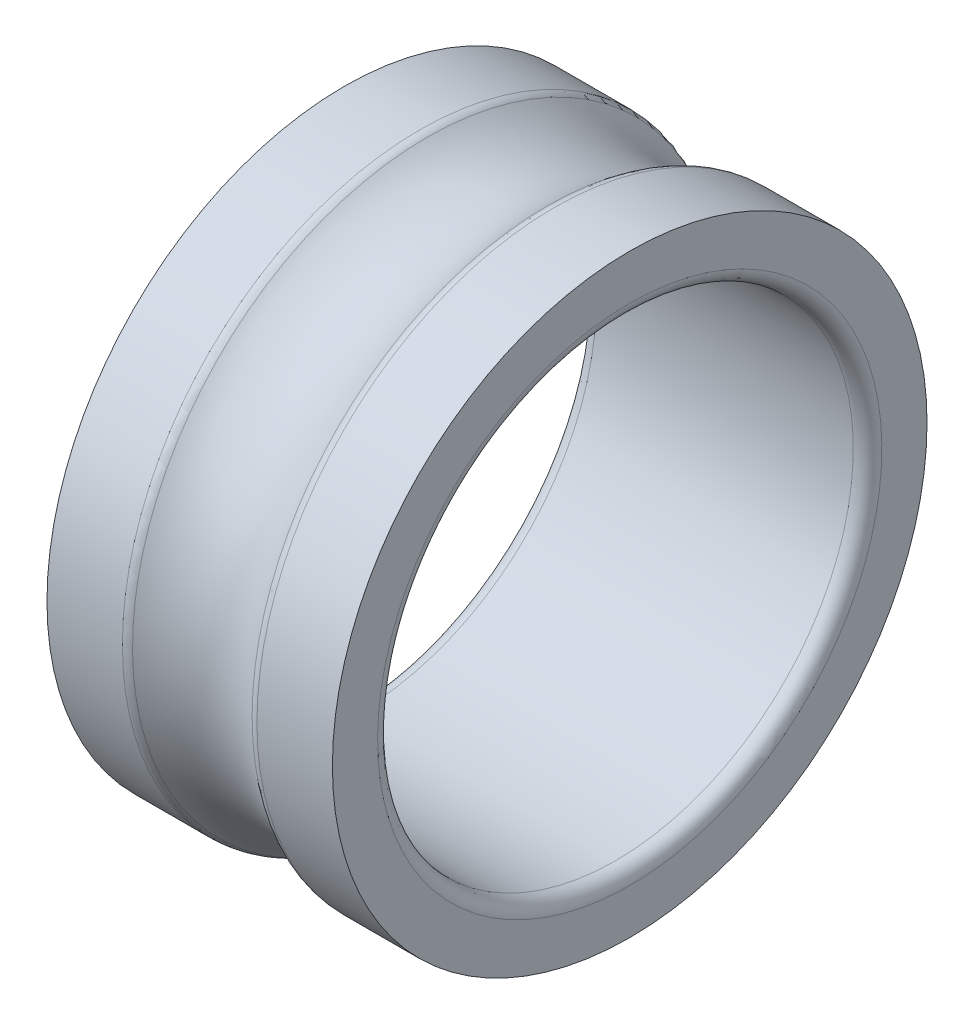
SolidWorks part; units mm, degrees
ref_plane "Front Plane" through (0, 0, 0) normal (0, 0, 1) x (1, 0, 0)
ref_plane "Top Plane" through (0, 0, 0) normal (0, 1, 0) x (1, 0, 0)
ref_plane "Right Plane" through (0, 0, 0) normal (1, 0, 0) x (0, 0, -1)
sketch "Sketch1" plane through (0, 0, 0) normal (0, 0, 1) x (1, 0, 0)
  line L0 (44.1264, 0) -> (-44.1264, 0) construction
  line L1 (-6, 10) -> (6, 10)
  line L2 (6, 10) -> (6, 12.5)
  line L3 (-6, 10) -> (-6, 12.5)
  line L4 (-6, 12.5) -> (6, 12.5)
  circle A0 centre (0, 15.5) radius 4
  point P2 (0, 0)
  point P9 (0, 10)
  dimension "D4" = 8
  dimension "D1" = 20
  dimension "D2" = 12
  dimension "D3" = 5.5
  dimension "D5" = 3
revolve "Revolve1" add sketch "Sketch1" angle 360 about L0
fillet "Fillet1" radius 0.6 2 edges at (6, 10, 0) (-6, 10, 0)
fillet "Fillet2" radius 0.5 2 edges at (2.6458, 12.5, 0) (-2.6458, 12.5, 0)
equation "\"d_ext_rouleau\"= 90"
equation "\"epaisseur_rouleau\"=80"
equation "\"alesage-rouleau\"= 52"
equation "\"jeu_dent_rouleau\"= 2"
equation "\"profondeur_dent_rouleau\"=4"
equation "\"n_dent_roueau\"= 15"
equation "\"d_ext_roulement_rouleau\"= 42"
equation "\"d_int_roulement_rouleau\"= 20"
equation "\"B_roulement_rouleau\"= 12"
equation "\"d_bille_roulement_rouleau\"= 8"
equation "\"F_anneau_alesage_rouleau\"=1.85"
equation "\"G_anneau_alesage_rouleau\"=47.5"
equation "\"K_anneau_alesage_rouleau\"=3.75"
equation "\"d_vis_flasque_rouleau\"=5"
equation "\"l-x_vis_flasque_rouleau\"=4"
equation "\"g_anneau_arbre_rouleau\"=19"
equation "\"f_anneau_arbre_rouleau\"=1.3"
equation "\"k_anneau_arbre_rouleau\"=1.5"
equation "\"h_matrice\"= 18"
equation "\"d_matrice\"= 220"
equation "\"d_granulat\"= 8"
equation "\"zone_vide_matrice\" = 48"
equation "\"d_alesage_matrice\"=20"
equation "\"a_clavette_alesage_matrice\"=6"
equation "\"entrax_vis_rouleau\"=65"
equation "\"D2@Sketch1\"=\"B_roulement_rouleau\""
equation "\"D1@Sketch1\"=\"d_int_roulement_rouleau\""
equation "\"D4@Sketch1\"=\"d_bille_roulement_rouleau\""
equation "\"D5@Sketch1\"=(\"d_bille_roulement_rouleau\"/2)-1"
equation "\"D3@Sketch1\"=(\"d_ext_roulement_rouleau\"-\"d_int_roulement_rouleau\")/4"
equation "\"r_roulement_rouleau\"= 0.6"
equation "\"D1@Fillet1\"=\"r_roulement_rouleau\""
